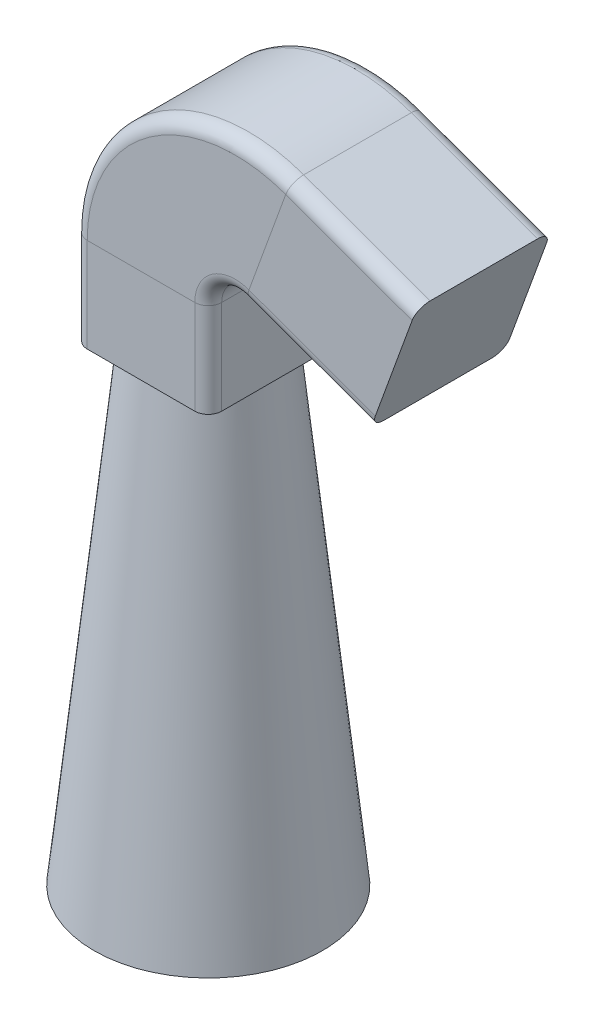
SolidWorks part; units mm, degrees
ref_plane "Front Plane" through (0, 0, 0) normal (0, 0, 1) x (1, 0, 0)
ref_plane "Top Plane" through (0, 0, 0) normal (0, 1, 0) x (1, 0, 0)
ref_plane "Right Plane" through (0, 0, 0) normal (1, 0, 0) x (0, 0, -1)
sketch "Sketch1" plane through (0, 0, 0) normal (1, 0, 0) x (0, 0, -1)
  line L0 (0, 13.1196) -> (0, 10.625) construction
  line L1 (0, 0) -> (8.5, 0)
  line L2 (8.5, 0) -> (4.8214, 35)
  line L3 (4.8214, 35) -> (0, 35)
  line L4 (0, 0) -> (0, 35)
  dimension "D1" = 8.5
  dimension "D2" = 35
  dimension "D3" = 6
revolve "Revolve1" add sketch "Sketch1" angle 360 about L0
sketch "Sketch2" plane through (0, 0, 0) normal (0, 0, 1) x (1, 0, 0)
  line L0 (0, 35) -> (0, 42.003)
  line L1 (9.3941, 48.5808) -> (18.7939, 45.1596)
  line L2 (4.8214, 35) -> (-4.8214, 35) construction
  line L3 (18.7939, 45.1596) -> (22.0342, 54.0623) construction
  arc A0 (9.3941, 48.5808) -> (0, 42.003) centre (7, 42.003) ccw
  point P10 (0, 52)
  dimension "D4" = 7
  dimension "D1" = 20
  dimension "D2" = 17
  dimension "D3" = 70
ref_plane "Plane1" through (2.0814, -0.7576, 0) normal (0.9397, -0.342, 0) x (0.342, 0.9397, 0)
sketch "Sketch4" plane through (2.0814, -0.7576, 0) normal (0.9397, -0.342, 0) x (0.342, 0.9397, 0)
  line L1 (43.864, 5) -> (53.864, 5)
  line L2 (43.864, 5) -> (43.864, -5)
  line L3 (43.864, -5) -> (53.864, -5)
  line L4 (53.864, 5) -> (53.864, -5)
  point P7 (51.1223, -5.1963)
  point P10 (51.7413, -1.8426)
  dimension "D1" = 10
  dimension "D2" = 10
  dimension "D3" = 5
  dimension "D4" = 5
sweep "Sweep1" add profiles "Sketch4" path "Sketch2"
fillet "Fillet1" radius 1 6 edges at (-5, 38.5015, 5) (15.8041, 51.5687, 5) (-5, 38.5015, -5) (0.1171, 51.8328, -5) (0.1171, 51.8328, 5) (15.8041, 51.5687, -5)
fillet "Fillet2" radius 1 6 edges at (12.3839, 42.1717, 5) (5.8528, 43.6413, 5) (12.3839, 42.1717, -5) (5.8528, 43.6413, -5) (5, 38.5015, 5) (5, 38.5015, -5)
